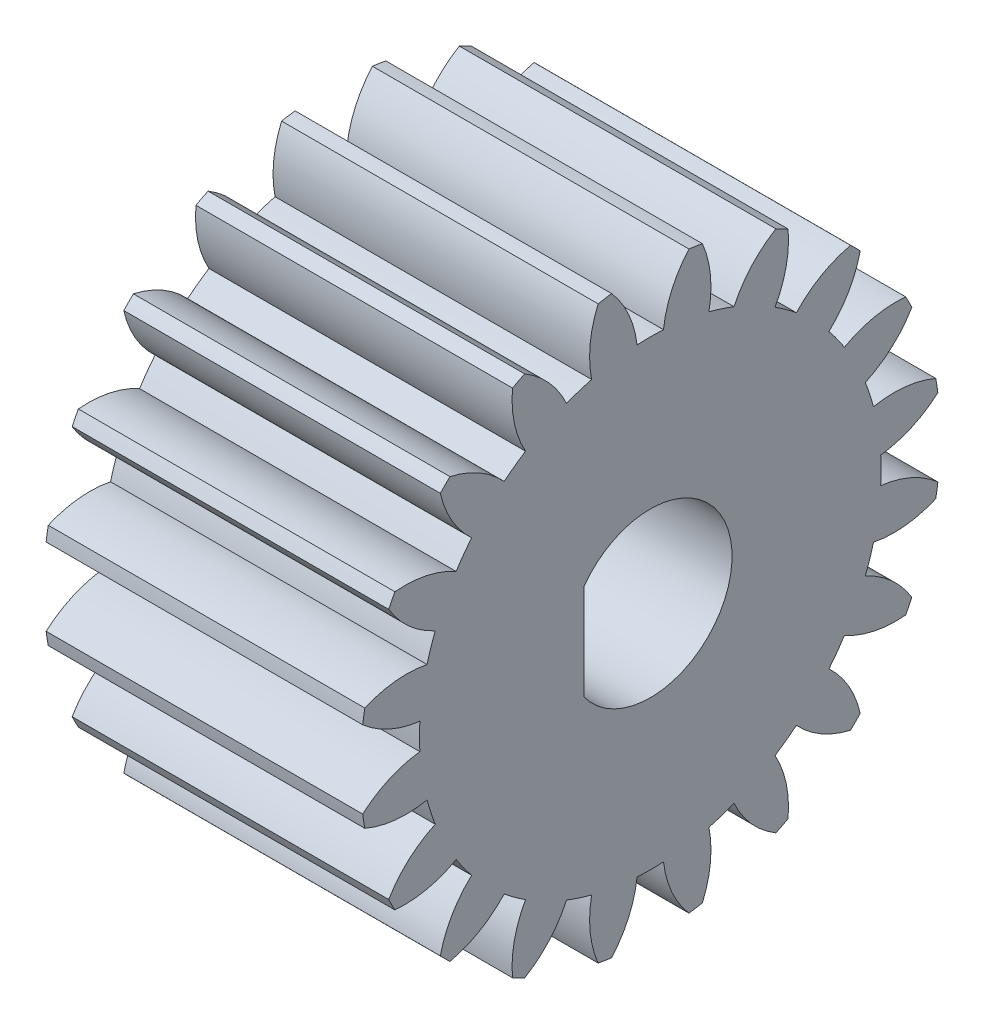
SolidWorks part; units mm, degrees
ref_plane "Plane1" through (0, 0, 0) normal (0, 0, 1) x (1, 0, 0)
ref_plane "Plane2" through (0, 0, 0) normal (0, 1, 0) x (1, 0, 0)
ref_plane "Plane3" through (0, 0, 0) normal (1, 0, 0) x (0, 0, -1)
other "Configuration Table"
sketch "HoldingSke" plane through (0, 0, 0) normal (0, 1, 0) x (1, 0, 0)
  line L0 (0, 0) -> (0.9397, -0.342)
  line L1 (-15, 0) -> (100, 0) construction
  line L2 (0, 0) -> (-2.1039, 2.3779)
  line L3 (0, 0) -> (-11.863, 4.5341)
  line L4 (0, 0) -> (8.1152, 2.9537)
  line L5 (0, 0) -> (-46.8476, -17.4728)
  line L6 (0, 0) -> (-9.9476, -6.7116)
  line L7 (-2.1039, 2.3779) -> (8.6586, 51.2059)
  line L8 (-76.2, 54.61) -> (-76.1, 54.61)
  line L9 (-71.009, 38.7566) -> (-53.1078, 45.2721)
  line L10 (-76.2, 71.12) -> (104.1128, 71.12)
  line L11 (0, 0) -> (-12, 0)
  line L12 (-76.2, 101.6) -> (-76.162, 101.6)
  line L13 (24.9733, 27.94) -> (52.9518, 28.4284)
  line L14 (24.9733, 27.94) -> (24.9743, 27.94)
  line L15 (24.9733, 27.94) -> (100.4006, 29.5858)
  line L16 (-63.627, -1) -> (-12.827, -1)
  circle A0 centre (0, 0) radius 0.4
  circle A1 centre (0, 0) radius 8.749
  circle A2 centre (0, 0) radius 37.5
  circle A3 centre (0, 0) radius 0.4
  dimension "MHD" = 17.498
  dimension "Hub_dia" = 75
  dimension "Bore" = 0.8
  dimension "MBD" = 0.8
  dimension "Num_teeth" = 20
  dimension "Pitch" = 1
  dimension "Overall_len" = 50
  dimension "Show_teeth" = 20
  dimension "Thickness" = 12
  dimension "OAL" = 50.0001
  dimension "T_dim" = 0.1
  dimension "Ap" = 20
  dimension "H" = 19.05
  dimension "Pitch_radius" = 180.3128
  dimension "Width" = 12
  dimension "Backlash" = 0.038
  dimension "Addendum_fac" = 1
  dimension "Dedendum_fac" = 1.25
  dimension "Clearance_fac" = 0.25
  dimension "Dedendum_add" = 0.001
  dimension "Module" = 1
sketch "BasProSke" plane through (0, 0, 0) normal (0, 1, 0) x (1, 0, 0)
  line L0 (-10, 0) -> (60, 0) construction
  line L1 (0, 0) -> (0, 11)
  line L2 (0, 0) -> (12, 0)
  line L3 (12, 0) -> (12, 11)
  line L4 (12, 11) -> (0, 11)
  dimension "Thickness" = 12
  dimension "Diameter" = 22
revolve "Base-Revolve" add sketch "BasProSke" angle 360 about L0
sketch "TooCutSke" plane through (0, 0, 0) normal (1, 0, 0) x (0, 0, -1)
  line L1 (0, 0) -> (0, 107) construction
  line L2 (0, 0) -> (-0.8511, 9.9637) construction
  line L3 (0, 0) -> (-3.1206, 19.7028) construction
  line L4 (-0.8511, 9.9637) -> (-1.5603, 9.8514) construction
  arc A0 (0.4999, 8.7347) -> (-0.4999, 8.7347) centre (0, 0) ccw
  arc A1 (1.4852, 10.9249) -> (-1.4852, 10.9249) centre (0, 0) ccw
  circle A2 centre (0, 0) radius 10 construction
  circle A3 centre (0, 0) radius 9.3969 construction
  arc A4 (-0.4999, 8.7347) -> (-1.4852, 10.9249) centre (-4.4722, 8.2645) ccw
  arc A5 (1.4852, 10.9249) -> (0.4999, 8.7347) centre (4.4722, 8.2645) ccw
  dimension "Root_dia" = 17.498
  dimension "Overcut_dia" = 22.0508
  dimension "Pitch_dia" = 20
  dimension "Base_dia" = 18.7939
  dimension "Flank_rad" = 4
  dimension "Half_ang" = 9
  dimension "Half_CT" = 0.7181
extrude "ToothCut" cut sketch "TooCutSke" along normal through all
fillet "Breaks" [suppressed] radius 0.02
fillet "RootFillets" [suppressed] radius 0.251
pattern_circular "TeethCuts" count 20 every 18 about axis through (-10, 0, 0) along (1, 0, 0) of "ToothCut", "RootFillets", "Breaks"
sketch "HubNeaOneSke" plane through (0, 0, 0) normal (-1, 0, 0) x (0, 0, 1)
  circle A0 centre (0, 0) radius 8.749
  dimension "Diameter" = 17.498
extrude "HubNearOne" [suppressed] add sketch "HubNeaOneSke" along normal blind 38.0001
sketch "HubNeaBotSke" plane through (0, 0, 0) normal (-1, 0, 0) x (0, 0, 1)
  circle A0 centre (0, 0) radius 8.749
  dimension "Diameter" = 17.498
extrude "HubNearBoth" [suppressed] add sketch "HubNeaBotSke" along normal blind 19
ref_plane "FarPln" through (12, 0, 0) normal (1, 0, 0) x (0, 0, -1)
sketch "HubFarSke" plane through (12, 0, 0) normal (1, 0, 0) x (0, 0, -1)
  circle A0 centre (0, 0) radius 8.749
  dimension "Diameter" = 17.498
extrude "HubFar" [suppressed] add sketch "HubFarSke" along normal blind 19
sketch "BorSke" plane through (0, 0, 0) normal (1, 0, 0) x (0, 0, -1)
  circle A0 centre (0, 0) radius 0.4
  dimension "Diameter" = 0.8
extrude "Bore" cut sketch "BorSke" along normal mid plane 100.0001
sketch "KeySke" plane through (0, 0, 0) normal (1, 0, 0) x (0, 0, -1)
  line L0 (-0.05, 0) -> (-0.05, 0.5)
  line L1 (-0.05, 0.5) -> (0.05, 0.5)
  line L2 (0.05, 0.5) -> (0.05, 0)
  line L3 (0, 0) -> (0, 34) construction
  line L4 (-0.05, 0) -> (0.05, 0)
  dimension "Offset" = 0.5
  dimension "Width" = 0.1
extrude "Keyway" [suppressed] cut sketch "KeySke" along normal mid plane 100.0001
pattern_circular "Keyway2" [suppressed] count 2 every 90 about axis through (-10, 0, 0) along (1, 0, 0)
sketch "Çizim1" plane through (12, 0, 0) normal (1, 0, 0) x (0, 0, -1)
  line L0 (-2.5203, 1.805) -> (-2.5203, -1.805)
  circle A0 centre (0, 0) radius 3.1
  dimension "D1" = 6.2
  dimension "D2" = 3.61
extrude "Kes-Ekstrüzyon1" cut sketch "Çizim1" against normal blind 20 contours L0 A0
equation "' \"Module@HoldingSke\" = 6.35"
equation "' \"Num_teeth@HoldingSke\" = 12"
equation "' \"Ap@HoldingSke\" =  20"
equation "' \"Ap@HoldingSke\" = 20"
equation "' \"Width@HoldingSke\" = 0.5 * 25.4"
equation "' \"Hub_dia@HoldingSke\"= 1 * 25.4"
equation "' \"Hub_dia@HoldingSke\" = 1 * 25.4"
equation "' \"Overall_len@HoldingSke\" = 1.0 * 25.4"
equation "' \"Bore@HoldingSke\" = 0.75 * 25.4"
equation "' \"T_dim@HoldingSke\" = 0.1 * 25.4"
equation "' \"Width@KeySke\" = 0.25 * 25.4"
equation "' \"Show_teeth@HoldingSke\" = 13"
equation "' \"Backlash@HoldingSke\" = 0.009 * 25.4"
equation "' \"Addendum_fac@HoldingSke\" = 1.0"
equation "' \"Dedendum_fac@HoldingSke\" = 1.25"
equation "' \"Dedendum_add@HoldingSke\" = 0.00005 * 25.4"
equation "' \"Clearance_fac@HoldingSke\" = 0.25"
equation "\"Pitch@HoldingSke\" = 1 / \"Module@HoldingSke\""
equation "\"Overcut_dia@TooCutSke\" = (\"Num_teeth@HoldingSke\" + 2 * \"Addendum_fac@HoldingSke\") / \"Pitch@HoldingSke\" + 0.002 * 25.4"
equation "\"Pitch_dia@TooCutSke\" = \"Num_teeth@HoldingSke\" / \"Pitch@HoldingSke\""
equation "\"Base_dia@TooCutSke\" = \"Num_teeth@HoldingSke\" / \"Pitch@HoldingSke\" * cos((\"Ap@HoldingSke\"  * 3.14159265 / 180))"
equation "\"Root_dia@TooCutSke\" = (\"Num_teeth@HoldingSke\" + 2) / \"Pitch@HoldingSke\" - 2 * (\"Addendum_fac@HoldingSke\" + \"Dedendum_fac@HoldingSke\") / \"Pitch@HoldingSke\" - \"Dedendum_add@HoldingSke\" * 2"
equation "\"Half_ang@TooCutSke\" = 180 / \"Num_teeth@HoldingSke\""
equation "\"Half_CT@TooCutSke\" = \"Num_teeth@HoldingSke\" / \"Pitch@HoldingSke\" * sin((3.14159265 / 2 / \"Num_teeth@HoldingSke\")) / 2 - 7 * \"Backlash@HoldingSke\" / 4"
equation "\"Flank_rad@TooCutSke\" = \"Num_teeth@HoldingSke\" / \"Pitch@HoldingSke\" / 5"
equation "\"Radius@RootFillets\" = \"Clearance_fac@HoldingSke\" / \"Pitch@HoldingSke\" + \"Dedendum_add@HoldingSke\""
equation "\"Break_rad@Breaks\" = 0.02 / \"Pitch@HoldingSke\""
equation "\"Thickness@HoldingSke\" = \"Width@HoldingSke\""
equation "\"OAL@HoldingSke\" = \"Thickness@HoldingSke\""
equation "\"MHD@HoldingSke\" = (\"Num_teeth@HoldingSke\" + 2) / \"Pitch@HoldingSke\" - 2 * (\"Addendum_fac@HoldingSke\" + \"Dedendum_fac@HoldingSke\")  / \"Pitch@HoldingSke\" - \"Dedendum_add@HoldingSke\" * 2"
equation "\"MBD@HoldingSke\" = (\"Num_teeth@HoldingSke\" + 2) / \"Pitch@HoldingSke\" - 2 * (\"Addendum_fac@HoldingSke\" + \"Dedendum_fac@HoldingSke\")  / \"Pitch@HoldingSke\" - \"Dedendum_add@HoldingSke\" * 2 - 0.002 * 25.4"
equation "\"MHD@HoldingSke\" = ((sgn( \"MHD@HoldingSke\" - \"Hub_dia@HoldingSke\" )-1)*( \"MHD@HoldingSke\" - \"Hub_dia@HoldingSke\" ))/-2+ \"Hub_dia@HoldingSke\""
equation "\"MBD@HoldingSke\" = ((sgn( \"MBD@HoldingSke\" - \"Bore@HoldingSke\" )-1)*( \"MBD@HoldingSke\" - \"Bore@HoldingSke\" ))/-2+ \"Bore@HoldingSke\""
equation "\"OAL@HoldingSke\" = ((sgn( \"OAL@HoldingSke\" - \"Overall_len@HoldingSke\" )+1)*( \"OAL@HoldingSke\" - \"Overall_len@HoldingSke\" ))/2 + \"Overall_len@HoldingSke\" + 0.000002 * 25.4"
equation "\"Num_teeth@TeethCuts\" = int( \"Show_teeth@HoldingSke\" ) + 1"
equation "\"Num_teeth@TeethCuts\" = ((sgn( \"Num_teeth@TeethCuts\" - \"Num_teeth@HoldingSke\" )-1)*( \"Num_teeth@TeethCuts\" - \"Num_teeth@HoldingSke\" ))/-2+ \"Num_teeth@HoldingSke\""
equation "\"Num_teeth@TeethCuts\" = ((sgn( \"Num_teeth@TeethCuts\" - 2.0)+1)*( \"Num_teeth@TeethCuts\" - 2.0))/2 +2.0"
equation "\"Angle@TeethCuts\" = 360.0 / \"Num_teeth@HoldingSke\""
equation "\"Diameter@BasProSke\" = (\"Num_teeth@HoldingSke\" + 2 * \"Addendum_fac@HoldingSke\") / \"Pitch@HoldingSke\""
equation "\"Thickness@BasProSke\"  = \"Thickness@HoldingSke\""
equation "' \"Fillet_rad@BasProSke\" =  \"Thickness@HoldingSke\" * 0.05"
equation "' \"Fillet_rad@BasProSke\" = \"Thickness@HoldingSke\" * 0.05"
equation "\"MHD@HoldingSke\" = ((sgn( \"MHD@HoldingSke\" - \"Root_dia@TooCutSke\" )-1)*( \"MHD@HoldingSke\" - \"Root_dia@TooCutSke\" ))/-2+ \"Root_dia@TooCutSke\""
equation "\"Diameter@HubNeaOneSke\" = \"MHD@HoldingSke\""
equation "\"Length@HubNearOne\" = \"OAL@HoldingSke\" - \"Thickness@BasProSke\""
equation "\"Diameter@HubNeaBotSke\" = \"MHD@HoldingSke\""
equation "\"Length@HubNearBoth\" = ( \"OAL@HoldingSke\" - \"Thickness@BasProSke\" ) / 2.0"
equation "\"Thickness@FarPln\" = \"Thickness@BasProSke\""
equation "\"Diameter@HubFarSke\" = \"MHD@HoldingSke\""
equation "\"Length@HubFar\" = ( \"OAL@HoldingSke\" - \"Thickness@BasProSke\" ) / 2.0"
equation "\"Diameter@BorSke\" = \"MBD@HoldingSke\""
equation "\"D1@Bore\" = \"OAL@HoldingSke\" * 2.0"
equation "\"D1@Keyway\" = \"OAL@HoldingSke\" * 2.0"
equation "\"Offset@KeySke\" = \"T_dim@HoldingSke\" + \"MBD@HoldingSke\" / 2.0"
